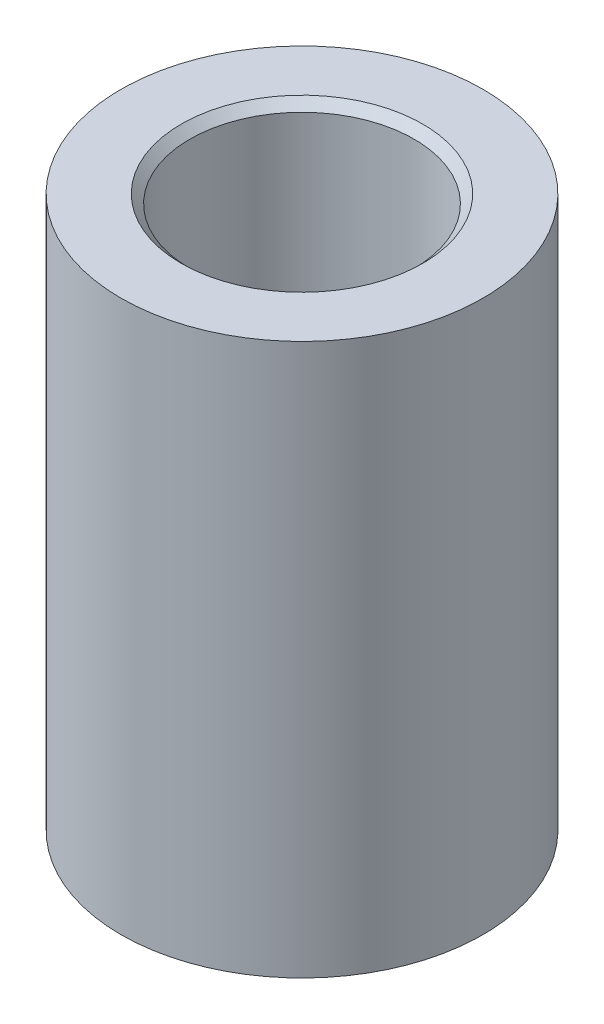
SolidWorks part; units mm, degrees
ref_plane "Front Plane" through (0, 0, 0) normal (0, 0, 1) x (1, 0, 0)
ref_plane "Top Plane" through (0, 0, 0) normal (0, 1, 0) x (1, 0, 0)
ref_plane "Right Plane" through (0, 0, 0) normal (1, 0, 0) x (0, 0, -1)
sketch "Sketch1" plane through (0, 0, 0) normal (0, 1, 0) x (1, 0, 0)
  circle A0 centre (0, 0) radius 5.1625
  circle A1 centre (0, 0) radius 8.3375
  dimension "D1" = 3.175
extrude "Boss-Extrude1" add sketch "Sketch1" along normal blind 25.4
chamfer "Chamfer1" distance 0.4 angle 45 2 edges at (0, 0, 5.1625) (0, 25.4, 5.1625)
